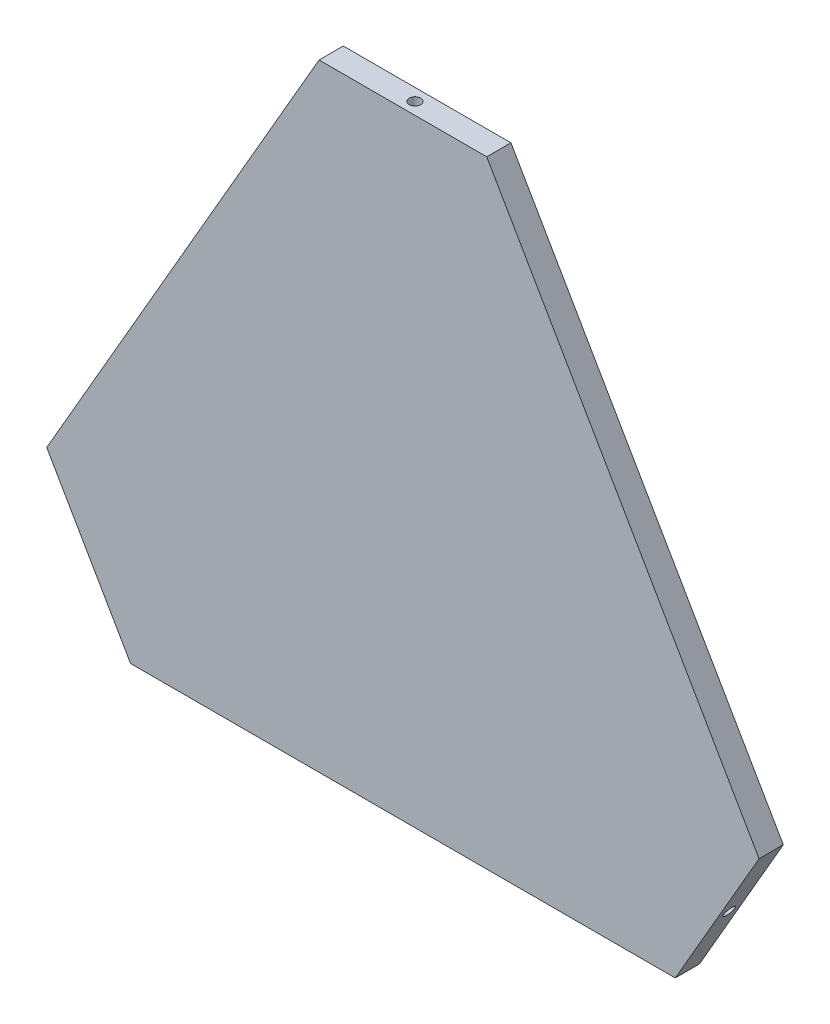
SolidWorks part; units mm, degrees
ref_plane "Plan de face" through (0, 0, 0) normal (0, 0, 1) x (1, 0, 0)
ref_plane "Plan de dessus" through (0, 0, 0) normal (0, 1, 0) x (1, 0, 0)
ref_plane "Plan de droite" through (0, 0, 0) normal (1, 0, 0) x (0, 0, -1)
sketch "Esquisse2" plane through (0, 0, 0) normal (0, 0, 1) x (1, 0, 0)
  line L0 (-115.4701, 0) -> (115.4701, 0)
  line L1 (115.4701, 0) -> (0, 200)
  line L2 (0, 200) -> (-115.4701, 0)
  point P4 (0, 0)
  dimension "D1" = 200
extrude "Boss.-Extru.1" add sketch "Esquisse2" along normal blind 6.35
sketch "Esquisse4" plane through (0, 0, 6.35) normal (0, 0, 1) x (1, 0, 0)
  line L0 (-115.4701, 0) -> (-93.4701, 38.1051)
  line L1 (0, 200) -> (-115.4701, 0) construction
  line L2 (-93.4701, 38.1051) -> (-71.4701, 0)
  line L3 (-115.4701, 0) -> (115.4701, 0) construction
  line L4 (-71.4701, 0) -> (-115.4701, 0)
  line L5 (115.4701, 0) -> (71.4701, 0)
  line L6 (71.4701, 0) -> (93.4701, 38.1051)
  line L7 (115.4701, 0) -> (0, 200) construction
  line L8 (93.4701, 38.1051) -> (115.4701, 0)
  line L9 (0, 200) -> (-22, 161.8949)
  line L10 (-22, 161.8949) -> (22, 161.8949)
  line L11 (22, 161.8949) -> (0, 200)
  dimension "D1" = 44
  dimension "D2" = 44
  dimension "D3" = 44
  dimension "D4" = 44
  dimension "D5" = 44
extrude "Enlèv. mat.-Extru.2" cut sketch "Esquisse4" against normal through all
sketch "Esquisse5" plane through (-53.6025, -30.9474, 0) normal (-0.866, -0.5, 0) x (0, 0, 1)
  line L0 (0, 79.735) -> (6.35, 79.735) construction
  line L1 (6.35, 35.735) -> (6.35, 79.735) construction
  circle A0 centre (3.175, 57.735) radius 1.5
  point P4 (3.175, 79.735)
  point P5 (0, 0)
  dimension "D1" = 22
  dimension "D3" = 3
  dimension "D2" = 3.175
extrude "Enlèv. mat.-Extru.3" cut sketch "Esquisse5" against normal blind 5
sketch "Esquisse7" plane through (0, 161.8949, 0) normal (0, 1, 0) x (1, 0, 0)
  line L0 (-22, 0) -> (22, 0) construction
  line L1 (22, 0) -> (22, -6.35) construction
  circle A0 centre (0, -3.175) radius 1.5
  dimension "D1" = 3.175
  dimension "D2" = 22
extrude "Enlèv. mat.-Extru.4" cut sketch "Esquisse7" against normal blind 5
sketch "Esquisse8" plane through (53.6025, -30.9474, 0) normal (0.866, -0.5, 0) x (0, 0, -1)
  line L0 (0, 79.735) -> (0, 35.735) construction
  line L1 (0, 79.735) -> (-6.35, 79.735) construction
  circle A0 centre (-3.175, 57.735) radius 1.5
  dimension "D1" = 3
  dimension "D3" = 22
  dimension "D2" = 3.175
extrude "Enlèv. mat.-Extru.5" cut sketch "Esquisse8" against normal blind 5
